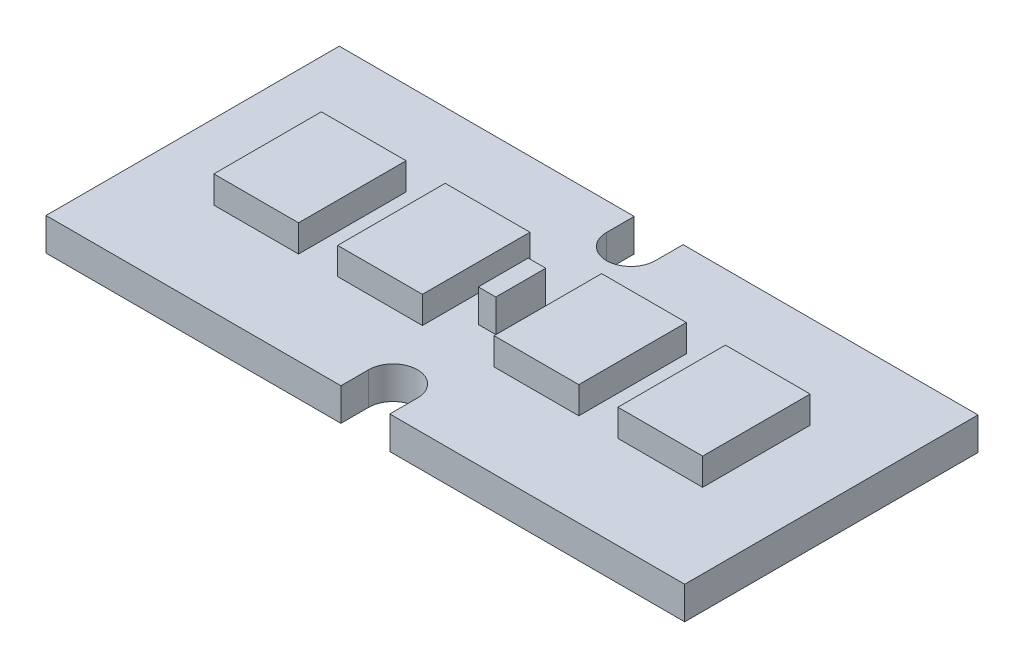
SolidWorks part; units mm, degrees
material "二氧化硅"
ref_plane "前视基准面" through (0, 0, 0) normal (0, 0, 1) x (1, 0, 0)
ref_plane "上视基准面" through (0, 0, 0) normal (0, 1, 0) x (1, 0, 0)
ref_plane "右视基准面" through (0, 0, 0) normal (1, 0, 0) x (0, 0, -1)
sketch "草图1" plane through (0, 0, 0) normal (0, 1, 0) x (1, 0, 0)
  line L1 (-9.8, 4.5) -> (9.8, 4.5)
  line L2 (-9.8, 4.5) -> (-9.8, -4.5)
  line L3 (-9.8, -4.5) -> (9.8, -4.5)
  line L4 (9.8, 4.5) -> (9.8, -4.5)
  line L5 (-9.8, 4.5) -> (9.8, -4.5) construction
  line L6 (-9.8, -4.5) -> (9.8, 4.5) construction
  point P0 (0, 0)
  dimension "D1" = 9
  dimension "D2" = 19.6
extrude "凸台-拉伸1" add sketch "草图1" along normal blind 1
sketch "草图2" plane through (0, 1, 0) normal (0, 1, 0) x (1, 0, 0)
  line L0 (-9.8, 0) -> (9.8, 0) construction
  line L1 (-9.8, 4.5) -> (-9.8, -4.5) construction
  line L2 (9.8, -4.5) -> (9.8, 4.5) construction
  line L3 (0, 0) -> (0, 7.2572) construction
  line L4 (9.8, 4.5) -> (-9.8, 4.5) construction
  line L5 (-0.75, 5.35) -> (0.75, 5.35)
  line L6 (-0.75, 5.35) -> (-0.75, 3.65)
  line L7 (-0.75, 3.65) -> (0.75, 3.65)
  line L8 (0.75, 5.35) -> (0.75, 3.65)
  line L9 (-0.75, 5.35) -> (0.75, 3.65) construction
  line L10 (-0.75, 3.65) -> (0.75, 5.35) construction
  line L11 (-0.75, -3.65) -> (0.75, -3.65)
  line L12 (0.75, -5.35) -> (0.75, -3.65)
  line L13 (-0.75, -5.35) -> (0.75, -5.35)
  line L14 (-0.75, -5.35) -> (-0.75, -3.65)
  circle A0 centre (0, 3.65) radius 0.75
  circle A1 centre (0, -3.65) radius 0.75
  point P9 (0, 4.5)
  line M4 (9.8, 4.5) -> (-9.8, 4.5)
  line M6 (-9.8, -4.5) -> (9.8, -4.5)
  dimension "D1" = 1.5
  dimension "D2" = 3.65
extrude "切除-拉伸1" cut sketch "草图2" against normal through all contours A0 L8 L6 M4 | L7 A0 | L7 A0 | A1 L11 | A1 L11 | L12 A1 L14 M6
sketch "草图3" plane through (0, 1, 0) normal (0, 1, 0) x (1, 0, 0)
  line L0 (0, 0) -> (0, 9.7383) construction
  line L2 (-0.2688, 0.765) -> (0.2688, 0.765)
  line L3 (-0.2688, 0.765) -> (-0.2688, -0.765)
  line L4 (-0.2688, -0.765) -> (0.2688, -0.765)
  line L5 (0.2688, 0.765) -> (0.2688, -0.765)
  line L6 (-0.2688, 0.765) -> (0.2688, -0.765) construction
  line L7 (-0.2688, -0.765) -> (0.2688, 0.765) construction
sketch "草图4" plane through (0, 1, 0) normal (0, 1, 0) x (1, 0, 0)
  line L0 (0, 0) -> (-10.3499, 0)
  line L1 (0, 0) -> (0, 9.7383) construction
  line L2 (-7.5, 1.65) -> (-4.9, 1.65)
  line L3 (-7.5, 1.65) -> (-7.5, -1.65)
  line L4 (-7.5, -1.65) -> (-4.9, -1.65)
  line L5 (-4.9, 1.65) -> (-4.9, -1.65)
  line L6 (-7.5, 1.65) -> (-4.9, -1.65) construction
  line L7 (-7.5, -1.65) -> (-4.9, 1.65) construction
  line L8 (0, 0) -> (0, 6.6021) construction
  line L9 (-3.7, 1.65) -> (-1.1, 1.65)
  line L10 (-3.7, 1.65) -> (-3.7, -1.65)
  line L11 (-3.7, -1.65) -> (-1.1, -1.65)
  line L12 (-1.1, 1.65) -> (-1.1, -1.65)
  line L13 (-3.7, 1.65) -> (-1.1, -1.65) construction
  line L14 (-3.7, -1.65) -> (-1.1, 1.65) construction
  line L15 (3.7, -1.65) -> (1.1, -1.65)
  line L16 (1.1, 1.65) -> (1.1, -1.65)
  line L17 (3.7, 1.65) -> (1.1, 1.65)
  line L18 (3.7, 1.65) -> (3.7, -1.65)
  line L19 (7.5, -1.65) -> (4.9, -1.65)
  line L20 (4.9, 1.65) -> (4.9, -1.65)
  line L21 (7.5, 1.65) -> (4.9, 1.65)
  line L22 (7.5, 1.65) -> (7.5, -1.65)
  point P3 (-6.2, 0)
  point P10 (-2.4, 0)
  dimension "D1" = 7.5
  dimension "D2" = 3.3
  dimension "D3" = 2.6
  dimension "D4" = 3.3
  dimension "D5" = 1.2
extrude "凸台-拉伸2" add sketch "草图4" along normal blind 0.83 contours L5 L2 L3 L0 | L5 L0 L3 L4 | L12 L9 L10 L0 | L12 L0 L10 L11 | L18 L17 L16 L15 | L22 L21 L20 L19
extrude "凸台-拉伸3" add sketch "草图3" along normal blind 1
